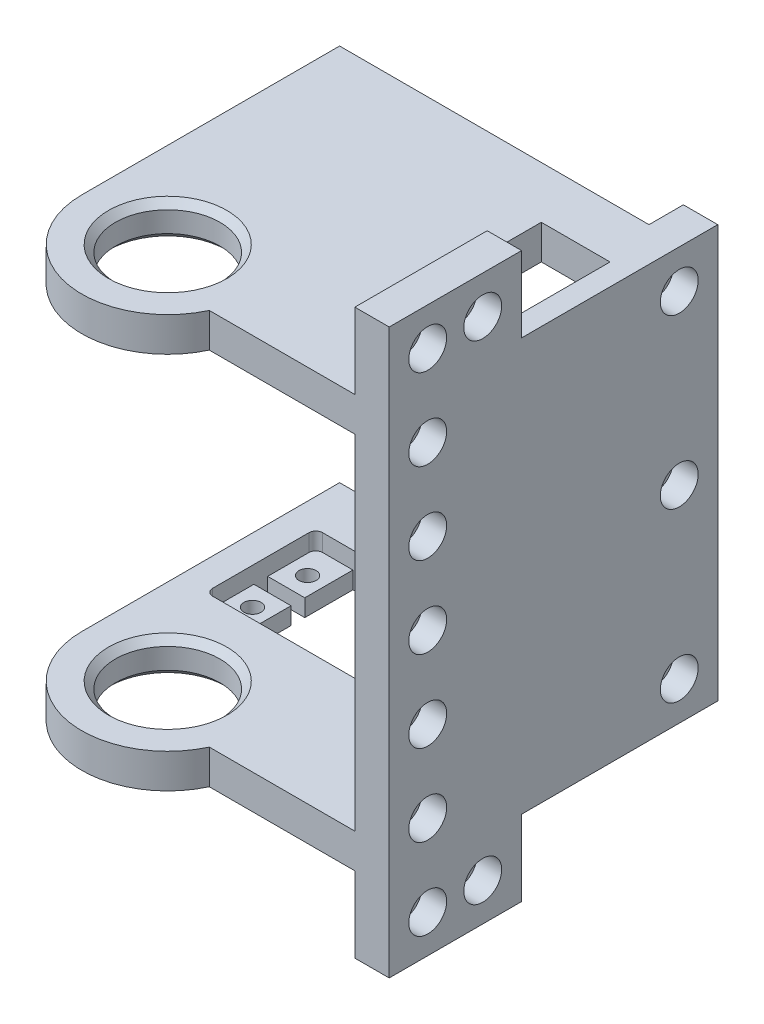
SolidWorks part; units mm, degrees
ref_plane "Front Plane" through (0, 0, 0) normal (0, 0, 1) x (1, 0, 0)
ref_plane "Top Plane" through (0, 0, 0) normal (0, 1, 0) x (1, 0, 0)
ref_plane "Right Plane" through (0, 0, 0) normal (1, 0, 0) x (0, 0, -1)
sketch "Sketch1" plane through (0, 0, 0) normal (0, 1, 0) x (1, 0, 0)
  line L0 (-15.2703, 47.625) -> (48.2297, 47.625)
  line L1 (48.2297, 47.625) -> (48.2297, -9.525)
  line L2 (48.2297, -9.525) -> (0.6047, -9.525)
  line L5 (-15.2703, 6.35) -> (-15.2703, 47.625)
  arc A1 (-15.2703, 6.35) -> (0.6047, -9.525) centre (0.6047, 6.35) ccw
  dimension "D3" = 63.5
  dimension "D4" = 15.875
  dimension "D5" = 57.15
extrude "Mass" add sketch "Sketch1" along normal blind 76.2
sketch "Sketch5" plane through (0, 0, 0) normal (0, -1, 0) x (1, 0, 0)
  circle A0 centre (0.6047, -6.35) radius 9.652
  arc A1 (0.6047, 9.525) -> (-15.2703, -6.35) centre (0.6047, -6.35) ccw construction
  dimension "D1" = 19.304
extrude "Bearing Hole" cut sketch "Sketch5" against normal through all
sketch "Sketch6" plane through (32.7805, 0, 9.525) normal (0, 0, -1) x (-1, 0, 0)
  line L1 (54.4007, 6.35) -> (-9.0993, 6.35)
  line L2 (54.4007, 6.35) -> (54.4007, 69.85)
  line L3 (54.4007, 69.85) -> (-9.0993, 69.85)
  line L4 (-9.0993, 6.35) -> (-9.0993, 69.85)
  line L7 (-15.4493, 76.2) -> (-15.4493, 0) construction
  line L8 (32.1757, 0) -> (-15.4493, 0) construction
  line L9 (32.1757, 76.2) -> (-15.4493, 76.2) construction
  dimension "D1" = 6.35
  dimension "D2" = 6.35
  dimension "D3" = 6.35
  dimension "D4" = 63.5
extrude "Hollow" cut sketch "Sketch6" along normal through all
sketch "Sketch2" plane through (0, 6.35, 0) normal (0, 1, 0) x (1, 0, 0)
  line L1 (-15.2703, 47.625) -> (-15.2703, 6.35) construction
  line L2 (48.2297, 47.625) -> (-15.2703, 47.625) construction
  line L5 (0.6047, 6.35) -> (6.7895, 34.2477) construction
  point P0 (0.6047, 6.35)
  line B0 (-3.2435, 24.0877) -> (37.3965, 24.0877)
  line B1 (-3.2435, 44.4077) -> (37.3965, 44.4077)
  circle B2 centre (-6.5455, 39.3327) radius 1.5875
  circle B3 centre (-6.5455, 29.1627) radius 1.5875
  circle B4 centre (40.6985, 39.3327) radius 1.5875
  circle B5 centre (40.6985, 29.1627) radius 1.5875
  line B6 (-3.2435, 24.0877) -> (-3.2435, 32.9777)
  line B7 (-3.2435, 44.4077) -> (-3.2435, 35.5177)
  line B8 (-3.2435, 32.9777) -> (-10.1015, 32.9777)
  line B9 (-10.1015, 32.9777) -> (-10.1015, 35.5177)
  line B10 (-10.1015, 35.5177) -> (-3.2435, 35.5177)
  line B11 (37.3965, 35.5177) -> (44.2545, 35.5177)
  line B12 (44.2545, 35.5177) -> (44.2545, 32.9777)
  line B13 (44.2545, 32.9777) -> (37.3965, 32.9777)
  line B14 (37.3965, 44.4077) -> (37.3965, 35.5177)
  line B15 (37.3965, 32.9777) -> (37.3965, 24.0877)
  dimension "D1" = 28.575
  dimension "D2" = 12.5
sketch_block_instance "Servo Mount ABS-1-1"
sketch_block "Servo Mount ABS-1" parameters "D5"=3.175, "D7"=1.8773, "D1"=22.86, "D2"=40.64, "D3"=10.17, "D4"=47.244, "D6"=10.033, "D8"=7.7865, "D9"=5.4364
extrude "Servo Mount" cut sketch "Sketch2" against normal blind 6.35
sketch "Sketch7" plane through (0, 6.35, 0) normal (0, 1, 0) x (1, 0, 0)
  line L1 (37.3965, 44.4077) -> (-3.2435, 44.4077) construction
  line L2 (-10.1015, 24.0877) -> (44.2545, 24.0877)
  line L3 (-10.1015, 24.0877) -> (-10.1015, 44.4077)
  line L4 (-10.1015, 44.4077) -> (44.2545, 44.4077)
  line L8 (44.2545, 24.0877) -> (44.2545, 44.4077)
  line L9 (-3.2435, 24.0877) -> (37.3965, 24.0877) construction
  line L10 (-10.1015, 35.5177) -> (-10.1015, 32.9777) construction
  line L11 (44.2545, 32.9777) -> (44.2545, 35.5177) construction
extrude "Servo Inset" cut sketch "Sketch7" against normal blind 3.175 and the other way up to surface (63.5 mm away) other way up to face at (0.6047, 69.85, -16.002)
chamfer "Bearing Chamfer" distance 1.27 angle 45 4 edges at (0.6047, 76.2, -16.002) (0.6047, 69.85, -16.002) (-9.0473, 6.35, -6.35) (0.6047, 0, -16.002)
fillet "Minor fillet" radius 1.27 5 edges at (-10.1015, 4.7625, -44.4077) (44.2545, 36.5125, -44.4077) (44.2545, 36.5125, -24.0877) (-10.1015, 4.7625, -24.0877) (44.2545, 69.85, -34.2477)
sketch "Sketch9" plane through (0, 6.35, 0) normal (0, 1, 0) x (1, 0, 0)
  line L0 (14.9924, -0.3591) -> (48.2297, -0.3591)
  line L2 (48.2297, -0.3591) -> (48.2297, -9.525)
  line L3 (48.2297, -9.525) -> (0.6047, -9.525)
  line L4 (14.9924, -0.3591) -> (0.6047, 6.35) construction
  line L5 (0.6047, 6.35) -> (0.6047, -9.525) construction
  line L7 (48.2297, -9.525) -> (48.2297, 47.625) construction
  arc A0 (0.6047, -9.525) -> (14.9924, -0.3591) centre (0.6047, 6.35) ccw
  dimension "D1" = 65
  dimension "D2" = 0
extrude "Cut-Extrude1" cut sketch "Sketch9" against normal through all and the other way through all
sketch "Sketch12" plane through (0, 69.85, 0) normal (0, -1, 0) x (1, 0, 0)
  line L0 (44.2545, -25.3577) -> (44.2545, -43.1377) construction
  line L1 (31.5545, -24.0877) -> (44.2545, -24.0877)
  line L2 (31.5545, -24.0877) -> (31.5545, -44.4077)
  line L3 (31.5545, -44.4077) -> (44.2545, -44.4077)
  line L4 (44.2545, -24.0877) -> (44.2545, -44.4077)
  line L5 (42.9845, -24.0877) -> (41.8797, -24.0877) construction
  line L6 (41.8797, -44.4077) -> (42.9845, -44.4077) construction
  dimension "D1" = 0
  dimension "D2" = 0
  dimension "D3" = 0
  dimension "D4" = 12.7
extrude "Cut-Extrude3" cut sketch "Sketch12" against normal through all and the other way blind 2.54
sketch "Sketch13" plane through (41.8797, 0, 0) normal (-1, 0, 0) x (0, 0, 1)
  line L1 (0.3591, 90.17) -> (-24.0877, 90.17)
  line L2 (0.3591, 90.17) -> (0.3591, -13.97)
  line L3 (0.3591, -13.97) -> (-24.0877, -13.97)
  line L4 (-24.0877, 90.17) -> (-24.0877, -13.97)
  line L5 (0.3591, 69.85) -> (0.3591, 6.35) construction
  line L6 (-24.0877, 69.85) -> (0.3591, 69.85) construction
  line L7 (-24.0877, 6.35) -> (0.3591, 6.35) construction
  line L8 (-24.0877, 69.85) -> (-24.0877, 6.35) construction
  dimension "D1" = 0
  dimension "D2" = 0
  dimension "D3" = 20.32
  dimension "D4" = 20.32
extrude "Boss-Extrude3" add sketch "Sketch13" against normal up to surface (6.35 mm away) up to face at (48.2297, 38.1, -23.633)
sketch "Sketch16" plane through (0, 0, -47.625) normal (0, 0, -1) x (-1, 0, 0)
  line L8 (-41.8797, 69.85) -> (15.2703, 69.85)
  line L9 (15.2703, 69.85) -> (15.2703, 76.2)
  line L10 (15.2703, 76.2) -> (-48.2297, 76.2)
  line L11 (-48.2297, 76.2) -> (-48.2297, 0)
  line L12 (-48.2297, 0) -> (15.2703, 0)
  line L13 (15.2703, 0) -> (15.2703, 6.35)
  line L14 (15.2703, 6.35) -> (-41.8797, 6.35)
  line L15 (-41.8797, 6.35) -> (-41.8797, 69.85)
  line L16 (-41.8797, 69.85) -> (15.2703, 69.85)
  line L17 (15.2703, 69.85) -> (15.2703, 76.2)
  line L18 (15.2703, 76.2) -> (-48.2297, 76.2)
  line L19 (-48.2297, 76.2) -> (-48.2297, 0)
  line L20 (-48.2297, 0) -> (15.2703, 0)
  line L21 (15.2703, 0) -> (15.2703, 6.35)
  line L22 (15.2703, 6.35) -> (-41.8797, 6.35)
  line L23 (-41.8797, 6.35) -> (-41.8797, 69.85)
  dimension "D1" = 0
extrude "Boss-Extrude4" add sketch "Sketch16" along normal blind 6.35
sketch "Sketch17" plane through (0, 0, -53.975) normal (0, 0, -1) x (-1, 0, 0)
  line L0 (-48.2297, 0) -> (15.2703, 0) construction
  line L1 (-48.2297, 76.2) -> (-41.8797, 76.2)
  line L2 (-48.2297, 76.2) -> (-48.2297, 0)
  line L3 (-48.2297, 0) -> (-41.8797, 0)
  line L4 (-41.8797, 76.2) -> (-41.8797, 0)
  line L5 (-41.8797, 6.35) -> (-41.8797, 69.85) construction
  dimension "D1" = 0
extrude "Boss-Extrude5" add sketch "Sketch17" along normal blind 6.35
sketch "Sketch18" plane through (48.2297, 0, 0) normal (1, 0, 0) x (0, 0, -1)
  line L0 (24.0877, -6.985) -> (-0.3591, -6.985) construction
  line L1 (24.0877, -13.97) -> (24.0877, 0) construction
  line L2 (-0.3591, -13.97) -> (-0.3591, 90.17) construction
  line L3 (24.0877, 83.185) -> (-0.3591, 83.185) construction
  line L4 (24.0877, 76.2) -> (24.0877, 90.17) construction
  line L5 (6.7529, -6.985) -> (6.7529, 83.185) construction
  line L6 (16.9129, -6.985) -> (16.9129, 83.185) construction
  line L7 (24.0877, 90.17) -> (-0.3591, 90.17) construction
  line L8 (24.0877, 76.2) -> (60.325, 76.2) construction
  line L9 (60.325, 76.2) -> (60.325, 0) construction
  line L10 (53.213, 69.088) -> (53.213, 0) construction
  line L11 (24.0877, 0) -> (60.325, 0) construction
  circle A0 centre (16.9129, -6.985) radius 3.5
  circle A1 centre (6.7529, -6.985) radius 3.5
  circle A2 centre (6.7529, 83.185) radius 3.5
  circle A3 centre (16.9129, 83.185) radius 3.5
  circle A4 centre (53.213, 69.088) radius 3.5
  circle A5 centre (53.213, 7.112) radius 3.5
  circle A6 centre (6.7529, 8.0433) radius 3.5
  circle A7 centre (6.7529, 23.0717) radius 3.5
  circle A8 centre (6.7529, 68.1567) radius 3.5
  circle A9 centre (6.7529, 53.1283) radius 3.5
  circle A10 centre (53.213, 38.1) radius 3.5
  circle A11 centre (6.7529, 38.1) radius 3.5
  dimension "D2" = 7
  dimension "D3" = 7
  dimension "D4" = 10.16
  dimension "D5" = 7.112
  dimension "D6" = 7
  dimension "D7" = 90.17
  dimension "D8" = 6.985
  dimension "D9" = 7.112
  dimension "D10" = 7.112
  dimension "D11" = 7
  dimension "D12" = 7
  dimension "D13" = 7.112
  dimension "D14" = 7
  dimension "D15" = 7
  dimension "D16" = 7
  dimension "D17" = 7
  dimension "D18" = 7
  dimension "D19" = 7
  dimension "D20" = 15.0283
  dimension "D21" = 15.0283
  dimension "D22" = 15.0283
  dimension "D23" = 15.0283
  dimension "D24" = 15.0283
  dimension "D1" = 24.4467
extrude "Cut-Extrude4" cut sketch "Sketch18" against normal blind 4.55
